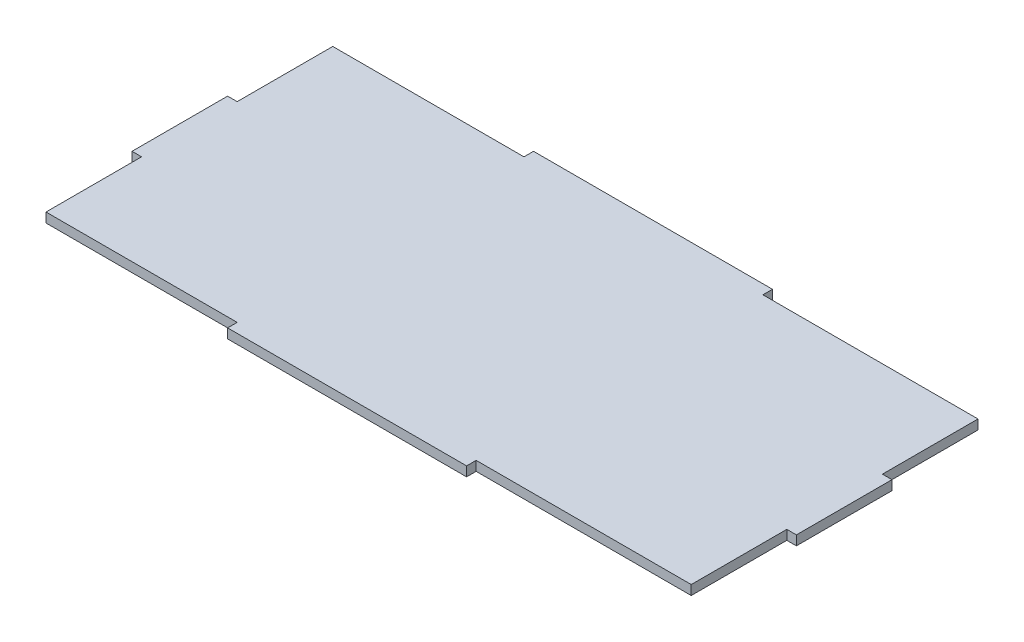
SolidWorks part; units mm, degrees
ref_plane "前视基准面" through (0, 0, 0) normal (0, 0, 1) x (1, 0, 0)
ref_plane "上视基准面" through (0, 0, 0) normal (0, 1, 0) x (1, 0, 0)
ref_plane "右视基准面" through (0, 0, 0) normal (1, 0, 0) x (0, 0, -1)
sketch "草图2" plane through (0, 0, 0) normal (0, 1, 0) x (1, 0, 0)
  line L0 (0, 30) -> (0, -30)
  line L1 (0, 30) -> (135, 30)
  line L2 (0, -30) -> (135, -30)
  line L3 (135, 30) -> (135, -30)
  line L4 (40, 32) -> (40, 30)
  line L5 (40, 32) -> (90, 32)
  line L6 (40, 30) -> (90, 30)
  line L7 (90, 32) -> (90, 30)
  line L8 (40, -30) -> (40, -32)
  line L9 (40, -30) -> (90, -30)
  line L10 (40, -32) -> (90, -32)
  line L11 (90, -30) -> (90, -32)
  line L12 (135, 10) -> (137, 10)
  line L13 (135, 10) -> (135, -10)
  line L14 (137, 10) -> (137, -10)
  line L15 (135, -10) -> (137, -10)
  line L16 (-2, 10) -> (-2, -10)
  line L17 (-2, 10) -> (0, 10)
  line L18 (-2, -10) -> (0, -10)
  line L19 (0, 10) -> (0, -10)
  point P0 (40, 30)
  point P3 (90, 30)
  point P4 (40, 32)
  point P5 (90, 32)
  point P6 (40, -32)
  point P7 (40, -30)
  point P8 (90, -30)
  point P12 (90, -32)
  point P13 (137, 10)
  point P18 (137, -10)
  point P19 (135, 10)
  point P20 (135, -10)
  point P21 (-2, 10)
  point P28 (-2, -10)
  point P29 (0, 10)
  point P30 (0, -10)
extrude "凸台-拉伸1" add sketch "草图2" along normal blind 2 contours L16 L18 L0 L17 | L7 L5 L4 L1 | L3 L15 L14 L12 | L11 L2 L8 L10 | L3 L1 L0 L2
